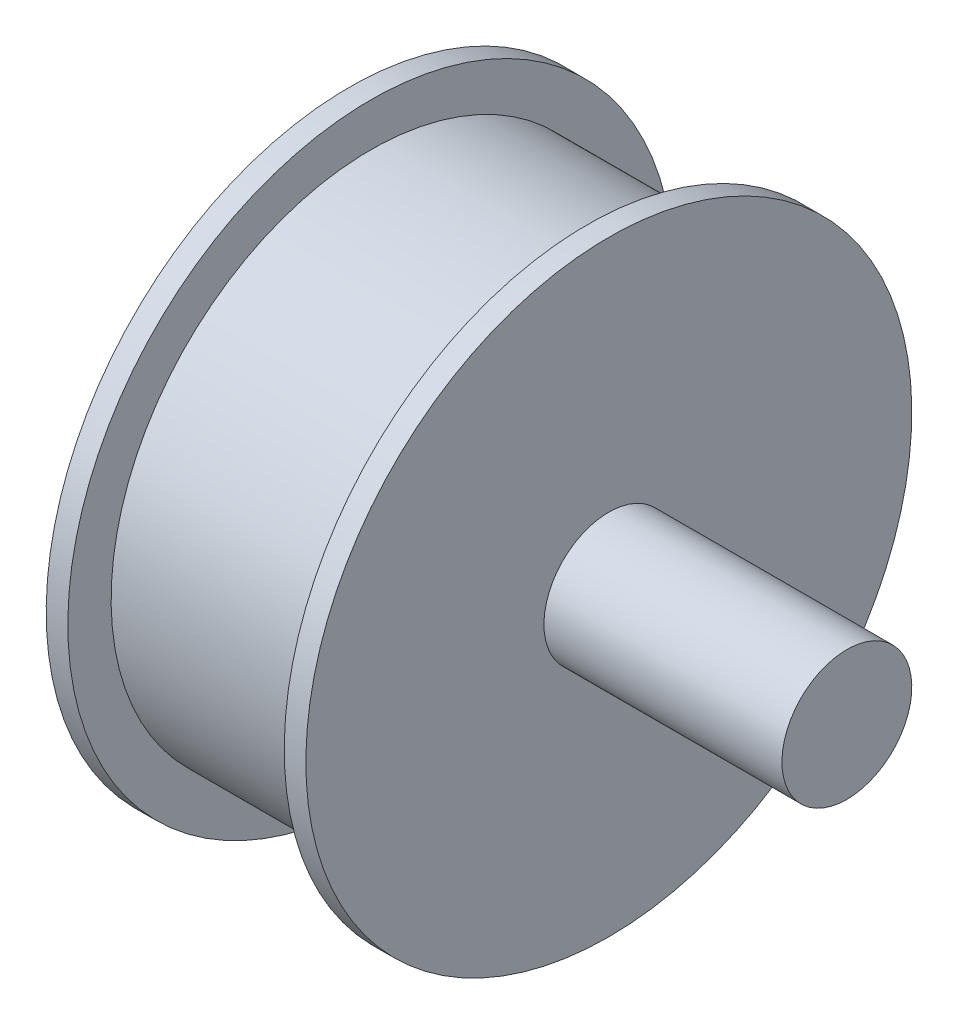
SolidWorks part; units mm, degrees
material "Plain Carbon Steel"
ref_plane "Front Plane" through (0, 0, 0) normal (0, 0, 1) x (1, 0, 0)
ref_plane "Top Plane" through (0, 0, 0) normal (0, 1, 0) x (1, 0, 0)
ref_plane "Right Plane" through (0, 0, 0) normal (1, 0, 0) x (0, 0, -1)
sketch "Sketch1" plane through (0, 0, 0) normal (0, 0, 1) x (1, 0, 0)
  line L0 (0, 7.5) -> (0, 35)
  line L1 (0, 35) -> (-2.5, 35)
  line L2 (-2.5, 35) -> (-2.5, 30)
  line L3 (-2.5, 30) -> (-27.5, 30)
  line L4 (-27.5, 30) -> (-27.5, 35)
  line L5 (-27.5, 35) -> (-30, 35)
  line L6 (-30, 35) -> (-30, 25)
  line L7 (-27.5, 0) -> (27.5, 0)
  line L8 (27.5, 0) -> (27.5, 7.5)
  line L9 (27.5, 7.5) -> (0, 7.5)
  line L10 (-27.5, 0) -> (-27.5, 5)
  line L11 (-30, 5) -> (-27.5, 5)
  line L13 (-30, 10) -> (-25, 10)
  line L14 (-25, 10) -> (-25, 25)
  line L15 (-25, 25) -> (-30, 25)
  line L16 (-30, 10) -> (-30, 5)
  dimension "D1" = 27.5
  dimension "D2" = 30
  dimension "D3" = 2.5
  dimension "D4" = 2.5
  dimension "D5" = 25
  dimension "D6" = 27.5
  dimension "D7" = 7.5
  dimension "D8" = 5
  dimension "D9" = 35
  dimension "D10" = 15
  dimension "D11" = 5
  dimension "D12" = 5
revolve "Revolve1" add sketch "Sketch1" angle 360 about L7
fillet "Fillet1" radius 1 1 edges at (-30, -10, 0)
